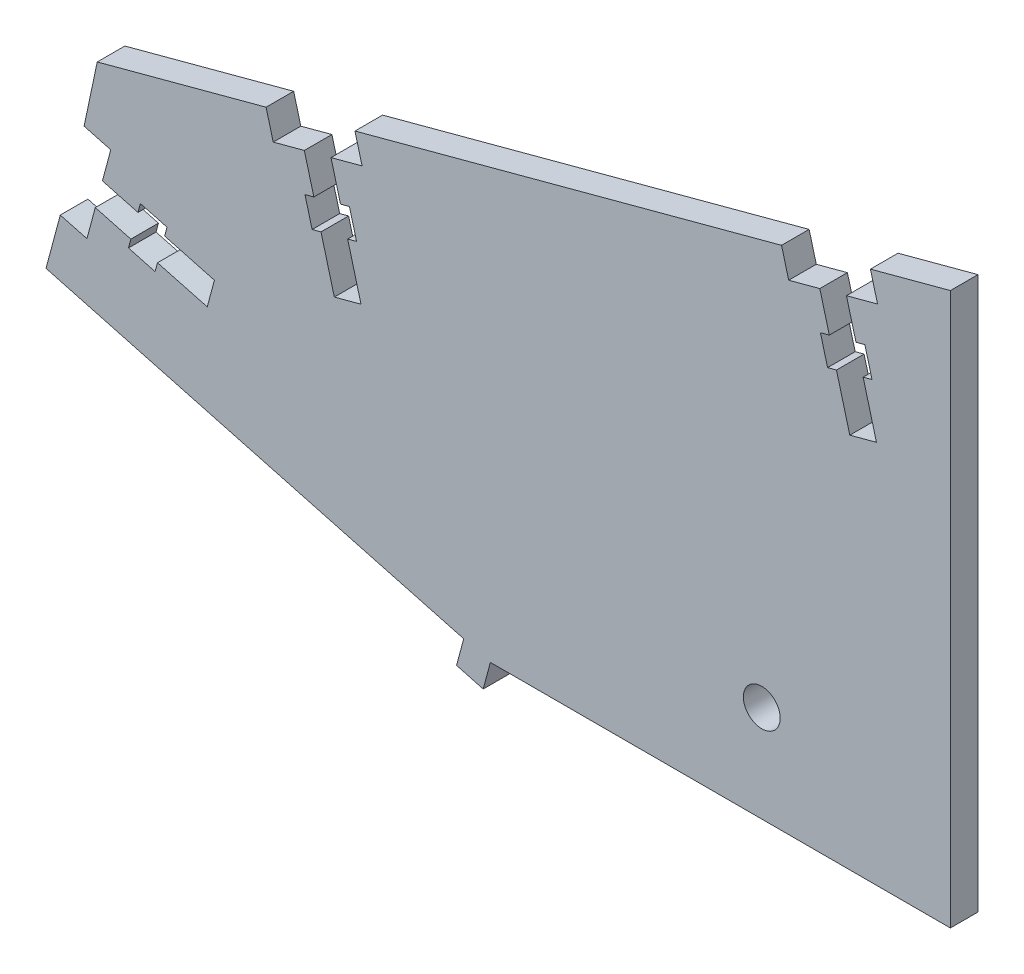
SolidWorks part; units mm, degrees
ref_plane "前视基准面" through (0, 0, 0) normal (0, 0, 1) x (1, 0, 0)
ref_plane "上视基准面" through (0, 0, 0) normal (0, 1, 0) x (1, 0, 0)
ref_plane "右视基准面" through (0, 0, 0) normal (1, 0, 0) x (0, 0, -1)
other "Configuration Table"
sketch "草图1" plane through (0, 0, 0) normal (0, 0, 1) x (1, 0, 0)
  line L0 (0, 0) -> (0, -60)
  line L1 (0, -60) -> (-50, -60)
  line L2 (0, 0) -> (-8.6933, -2.3294)
  line L3 (-4.3467, -1.1647) -> (-1.2395, -12.7607) construction
  line L4 (-8.6933, -2.3294) -> (-7.9169, -5.2271)
  line L5 (-7.9169, -5.2271) -> (-11.2976, -6.133)
  line L6 (-11.2976, -6.133) -> (-10.2623, -9.9967)
  line L7 (-10.2623, -9.9967) -> (-9.2964, -9.7379)
  line L8 (-9.2964, -9.7379) -> (-8.52, -12.6357)
  line L9 (-8.52, -12.6357) -> (-9.4859, -12.8945)
  line L10 (-9.4859, -12.8945) -> (-8.0365, -18.3037)
  line L11 (-8.0365, -18.3037) -> (-10.9343, -19.0801)
  line L12 (-10.9343, -19.0801) -> (-12.3837, -13.671)
  line L13 (-12.3837, -13.671) -> (-13.3496, -13.9298)
  line L14 (-13.3496, -13.9298) -> (-14.126, -11.032)
  line L15 (-14.126, -11.032) -> (-13.1601, -10.7732)
  line L16 (-13.1601, -10.7732) -> (-14.1954, -6.9095)
  line L17 (-8.6933, -2.3294) -> (-3.5131, -0.9413) construction
  line L18 (-14.1954, -6.9095) -> (-17.5761, -7.8153)
  line L19 (-17.5761, -7.8153) -> (-18.3526, -4.9176)
  line L20 (-18.3526, -4.9176) -> (-64.717, -17.3409)
  line L21 (-64.717, -17.3409) -> (-51.0207, -13.671) construction
  line L22 (-51.0207, -13.671) -> (-49.5713, -19.0801) construction
  line L23 (-64.717, -17.3409) -> (-63.9406, -20.2387)
  line L24 (-63.9406, -20.2387) -> (-67.3213, -21.1445)
  line L25 (-67.3213, -21.1445) -> (-66.286, -25.0082)
  line L26 (-66.286, -25.0082) -> (-65.3201, -24.7494)
  line L27 (-65.3201, -24.7494) -> (-64.5437, -27.6472)
  line L28 (-64.5437, -27.6472) -> (-65.5096, -27.906)
  line L29 (-65.5096, -27.906) -> (-64.0602, -33.3152)
  line L30 (-64.0602, -33.3152) -> (-66.958, -34.0916)
  line L31 (-66.958, -34.0916) -> (-68.4074, -28.6825)
  line L32 (-68.4074, -28.6825) -> (-69.3733, -28.9413)
  line L33 (-69.3733, -28.9413) -> (-70.1497, -26.0435)
  line L34 (-70.1497, -26.0435) -> (-69.1838, -25.7847)
  line L35 (-69.1838, -25.7847) -> (-70.2191, -21.921)
  line L36 (-70.2191, -21.921) -> (-73.5998, -22.8268)
  line L37 (-73.5998, -22.8268) -> (-74.3763, -19.9291)
  line L38 (-74.3763, -19.9291) -> (-92.7289, -24.8466)
  line L39 (-52.8978, -59.2235) -> (-98.2963, -47.059)
  line L40 (-50, -60) -> (-50.7765, -62.8978)
  line L41 (-50.7765, -62.8978) -> (-53.6742, -62.1213)
  line L42 (-53.6742, -62.1213) -> (-52.8978, -59.2235)
  line L43 (-98.2963, -47.059) -> (-81.3354, -51.6037) construction
  line L44 (-75.597, -53.1413) -> (-73.0136, -43.5) construction
  line L45 (-98.2963, -47.059) -> (-96.7434, -41.2635)
  line L46 (-96.7434, -41.2635) -> (-98.2963, -47.059) construction
  line L47 (-96.7434, -41.2635) -> (-93.8456, -42.0399)
  line L48 (-93.8456, -42.0399) -> (-92.9397, -38.6592)
  line L49 (-92.9397, -38.6592) -> (-89.076, -39.6945)
  line L50 (-89.076, -39.6945) -> (-89.3348, -40.6604)
  line L51 (-89.3348, -40.6604) -> (-86.4371, -41.4369)
  line L52 (-86.4371, -41.4369) -> (-86.1783, -40.4709)
  line L53 (-86.1783, -40.4709) -> (-80.7691, -41.9203)
  line L54 (-80.7691, -41.9203) -> (-79.9926, -39.0226)
  line L55 (-79.9926, -39.0226) -> (-85.4018, -37.5732)
  line L56 (-85.4018, -37.5732) -> (-85.143, -36.6072)
  line L57 (-85.143, -36.6072) -> (-88.0408, -35.8308)
  line L58 (-88.0408, -35.8308) -> (-88.2996, -36.7967)
  line L59 (-88.2996, -36.7967) -> (-92.1633, -35.7614)
  line L60 (-92.1633, -35.7614) -> (-91.2574, -32.3807)
  line L61 (-91.2574, -32.3807) -> (-94.1552, -31.6042)
  line L62 (-94.1552, -31.6042) -> (-92.7289, -24.8466)
  circle A0 centre (-20.5, -49.5) radius 2
  dimension "D16" = 3
  dimension "D43" = 4
  dimension "D1" = 60
  dimension "D2" = 50
  dimension "D3" = 9
  dimension "D4" = 75
  dimension "D5" = 3
  dimension "D6" = 3.5
  dimension "D7" = 4
  dimension "D8" = 1
  dimension "D9" = 3
  dimension "D10" = 1
  dimension "D11" = 5.6
  dimension "D12" = 3
  dimension "D13" = 1
  dimension "D14" = 3.5
  dimension "D15" = 48
  dimension "D17" = 3.5
  dimension "D18" = 4
  dimension "D19" = 1
  dimension "D20" = 3
  dimension "D21" = 1
  dimension "D22" = 5.6
  dimension "D23" = 3
  dimension "D24" = 1
  dimension "D25" = 3.5
  dimension "D26" = 19
  dimension "D27" = 50
  dimension "D28" = 165
  dimension "D29" = 3
  dimension "D30" = 3
  dimension "D31" = 6
  dimension "D32" = 90
  dimension "D33" = 3
  dimension "D34" = 3.5
  dimension "D35" = 4
  dimension "D36" = 1
  dimension "D37" = 3
  dimension "D38" = 1
  dimension "D39" = 5.6
  dimension "D40" = 3
  dimension "D41" = 1
  dimension "D42" = 3.5
  dimension "D44" = 20.5
  dimension "D45" = 10.5
extrude "凸台-拉伸1" add sketch "草图1" along normal blind 3
